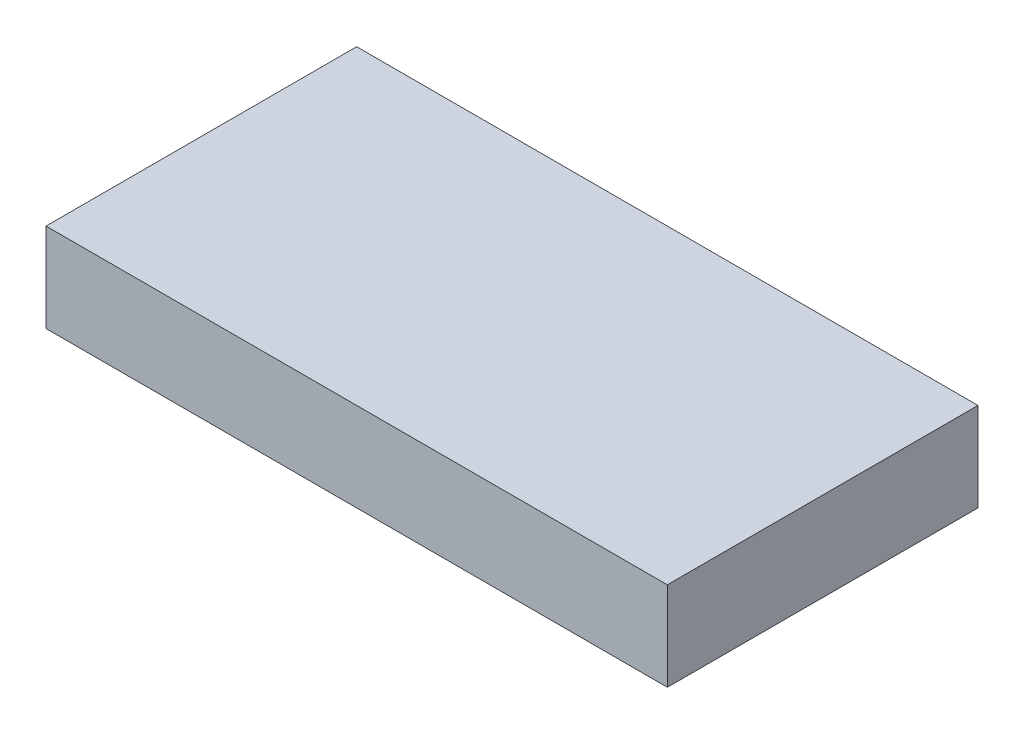
SolidWorks part; units mm, degrees
ref_plane "Front Plane" through (0, 0, 0) normal (0, 0, 1) x (1, 0, 0)
ref_plane "Top Plane" through (0, 0, 0) normal (0, 1, 0) x (1, 0, 0)
ref_plane "Right Plane" through (0, 0, 0) normal (1, 0, 0) x (0, 0, -1)
sketch "Sketch1" plane through (0, 0, 0) normal (0, 1, 0) x (1, 0, 0)
  line L1 (-88.9, -44.45) -> (88.9, -44.45)
  line L2 (-88.9, -44.45) -> (-88.9, 44.45)
  line L3 (-88.9, 44.45) -> (88.9, 44.45)
  line L4 (88.9, -44.45) -> (88.9, 44.45)
  line L5 (-88.9, -44.45) -> (88.9, 44.45) construction
  line L6 (-88.9, 44.45) -> (88.9, -44.45) construction
  point P0 (0, 0)
  dimension "D1" = 177.8
  dimension "D2" = 88.9
extrude "Boss-Extrude1" add sketch "Sketch1" along normal blind 25.4 contours L3 L4 L1 L2
